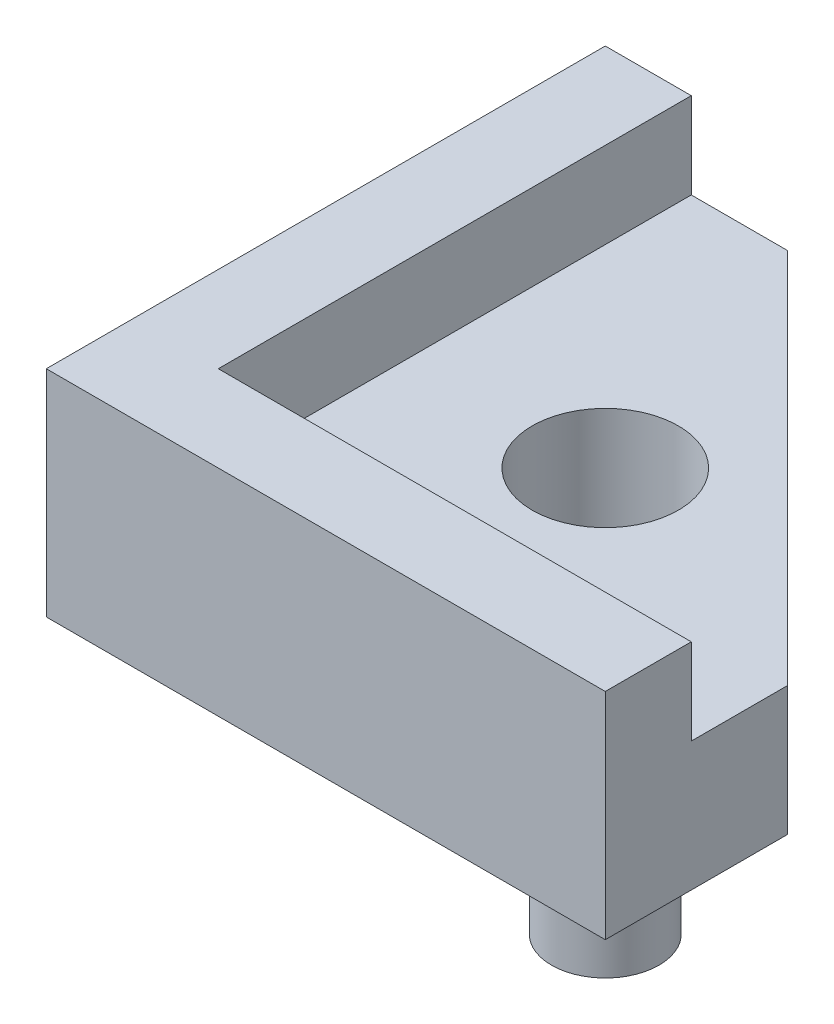
SolidWorks part; units mm, degrees
material "PET"
ref_plane "Front Plane" through (0, 0, 0) normal (0, 0, 1) x (1, 0, 0)
ref_plane "Top Plane" through (0, 0, 0) normal (0, 1, 0) x (1, 0, 0)
ref_plane "Right Plane" through (0, 0, 0) normal (1, 0, 0) x (0, 0, -1)
sketch "Board" plane through (0, 0, 0) normal (0, 1, 0) x (1, 0, 0)
  line L8 (0, 0) -> (85, 0) construction
  line L9 (0, 0) -> (0, 85) construction
  line L10 (0, 85) -> (85, 85) construction
  line L11 (85, 0) -> (85, 85) construction
  circle A1 centre (4, 4) radius 1.6 construction
  dimension "D3" = 3.2
  dimension "D1" = 85
  dimension "D2" = 85
  dimension "D4" = 4
  dimension "D5" = 4
sketch "Sketch3" plane through (0, 0, 0) normal (0, 1, 0) x (1, 0, 0)
  line L0 (-2.5, 10.5) -> (-2.5, -2.5)
  line L1 (-2.5, -2.5) -> (10.5, -2.5)
  line L2 (10.5, -2.5) -> (10.5, 1.7426)
  line L3 (10.5, 1.7426) -> (1.7426, 10.5)
  line L4 (1.7426, 10.5) -> (-2.5, 10.5)
  line L5 (0, 0) -> (0, 85) construction
  line L6 (0, 0) -> (85, 0) construction
  dimension "D1" = 2.5
  dimension "D2" = 2.5
  dimension "D3" = 45
  dimension "D4" = 13
  dimension "D5" = 13
  dimension "D6" = 3
extrude "Boss-Extrude2" add sketch "Sketch3" against normal blind 3
sketch "Sketch4" plane through (0, -3, 0) normal (0, -1, 0) x (1, 0, 0)
  line L2 (0.1109, -7.8891) -> (7.8891, -0.1109) construction
  line L3 (10.5, -1.7426) -> (1.7426, -10.5) construction
  circle A0 centre (7.8891, -0.1109) radius 1.25
  circle A1 centre (0.1109, -7.8891) radius 1.25
  dimension "D1" = 2.5
  dimension "D2" = 11
extrude "Boss-Extrude3" add sketch "Sketch4" along normal blind 2.5
sketch "Sketch5" plane through (0, 0, 0) normal (0, 1, 0) x (1, 0, 0)
  line L0 (-2.5, 10.5) -> (-2.5, -2.5)
  line L1 (-2.5, -2.5) -> (10.5, -2.5)
  line L2 (10.5, -2.5) -> (10.5, -0.5)
  line L3 (10.5, -2.5) -> (10.5, 1.7426) construction
  line L4 (10.5, -0.5) -> (-0.5, -0.5)
  line L5 (-0.5, -0.5) -> (-0.5, 10.5)
  line L7 (-0.5, 10.5) -> (-2.5, 10.5)
  line L9 (0, 0) -> (0, 85) construction
  line L10 (0, 0) -> (85, 0) construction
  dimension "D1" = 0.5
  dimension "D2" = 0.5
extrude "Boss-Extrude4" add sketch "Sketch5" along normal blind 2
sketch "Sketch6" plane through (0, 0, 0) normal (0, 1, 0) x (1, 0, 0)
  circle A0 centre (4, 4) radius 1.7
  dimension "D1" = 3.4
extrude "Cut-Extrude1" cut sketch "Sketch6" against normal up to next
